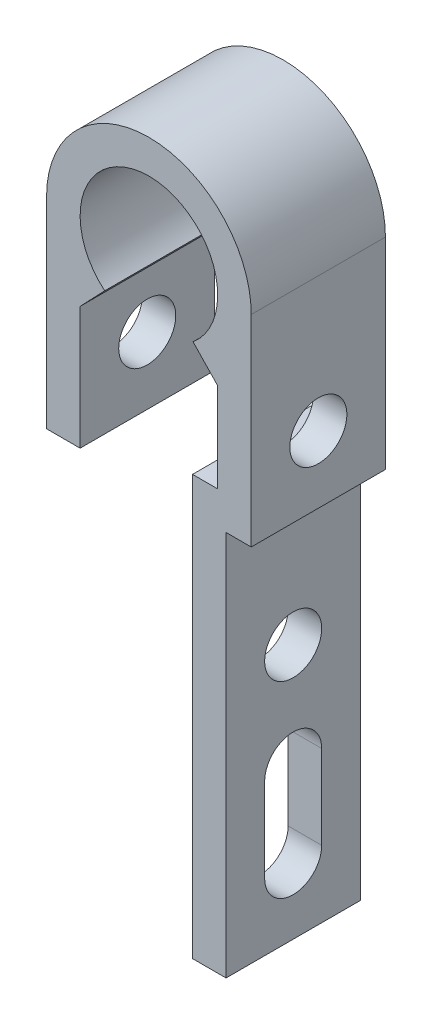
SolidWorks part; units mm, degrees
material "ABS"
ref_plane "Plano frontal" through (0, 0, 0) normal (0, 0, 1) x (1, 0, 0)
ref_plane "Plano superior" through (0, 0, 0) normal (0, 1, 0) x (1, 0, 0)
ref_plane "Plano direito" through (0, 0, 0) normal (1, 0, 0) x (0, 0, -1)
sketch "Esboço1" plane through (0, 0, 0) normal (0, 0, 1) x (1, 0, 0)
  line L0 (4.1, -4.6769) -> (2.6354, -3.1408)
  line L1 (4.1, -4.6769) -> (4.1, -10)
  line L2 (4.1, -10) -> (2.6, -10)
  line L3 (2.6, -10) -> (2.6, -35)
  line L4 (-6.1, -12) -> (-6.1, 0)
  line L5 (6.1, 0) -> (6.1, -12)
  line L6 (6.1, -12) -> (4.6, -12)
  line L7 (4.6, -12) -> (4.6, -35)
  line L8 (-6.1, -12) -> (-4.1, -12)
  line L9 (2.6, -35) -> (4.6, -35)
  line L10 (2.6, -10) -> (-3.7, -10) construction
  line L11 (-3.7, -10) -> (-3.7, -35) construction
  line L12 (-3.7, -35) -> (2.6, -35) construction
  line L13 (-4.1, -12) -> (-4.1, -4.6769)
  line L14 (-2.6354, -3.1408) -> (-4.1, -4.6769)
  arc A0 (-2.6354, -3.1408) -> (2.6354, -3.1408) centre (0, 0) cw
  arc A1 (-6.1, 0) -> (6.1, 0) centre (0, 0) cw
  dimension "D1" = 4.1
  dimension "D5" = 2
  dimension "D2" = 1.5
  dimension "D3" = 2
  dimension "D4" = 25
  dimension "D6" = 12
  dimension "D7" = 6.3
  dimension "D8" = 2
  dimension "D9" = 2
  dimension "D10" = 2
  dimension "D11" = 80
extrude "Ressalto-extrusão1" add sketch "Esboço1" along normal blind 8
sketch "Esboço2" plane through (-6.1, 0, 0) normal (-1, 0, 0) x (0, 0, 1)
  line L0 (4, -26) -> (4, -31) construction
  line L1 (5.7, -26) -> (5.7, -31)
  line L2 (2.3, -26) -> (2.3, -31)
  line L3 (8, -10) -> (0, -10) construction
  line L6 (8, -12) -> (0, -12) construction
  line L7 (0, 0) -> (0, -4.2) construction
  line L8 (0, 0) -> (0, -12) construction
  line L9 (0, -4.2) -> (8, -4.2) construction
  line L10 (8, 0) -> (8, -12) construction
  line L11 (8, -35) -> (0, -35) construction
  circle A0 centre (4, -8) radius 1.7
  circle A1 centre (4, -19.8) radius 1.7
  arc A2 (5.7, -26) -> (2.3, -26) centre (4, -26) ccw
  arc A3 (2.3, -31) -> (5.7, -31) centre (4, -31) ccw
  point P6 (4, -28.5)
  point P16 (4, -10)
  dimension "D1" = 7
  dimension "D2" = 3.4
  dimension "D3" = 5
  dimension "D4" = 4
  dimension "D5" = 4
  dimension "D6" = 4.2
extrude "Corte-extrusão1" cut sketch "Esboço2" against normal through all
